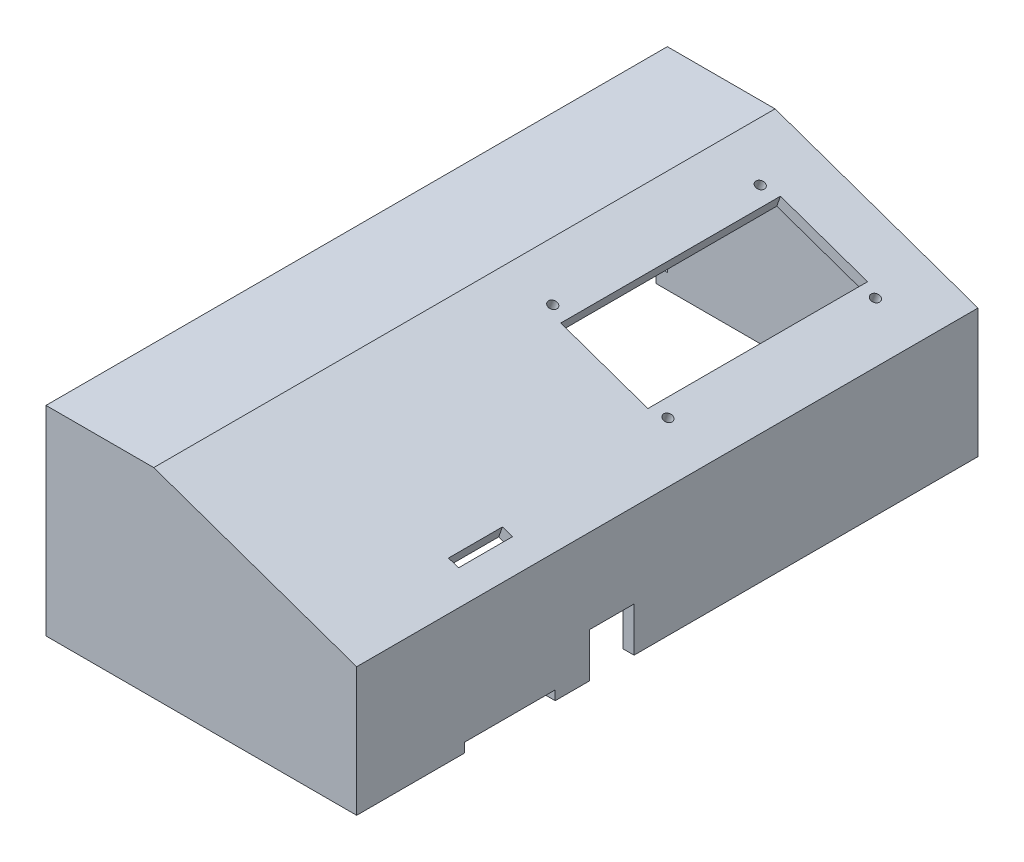
SolidWorks part; units mm, degrees
ref_plane "Front Plane" through (0, 0, 0) normal (0, 0, 1) x (1, 0, 0)
ref_plane "Top Plane" through (0, 0, 0) normal (0, 1, 0) x (1, 0, 0)
ref_plane "Right Plane" through (0, 0, 0) normal (1, 0, 0) x (0, 0, -1)
sketch "Sketch1" plane through (0, 0, 0) normal (0, 0, 1) x (1, 0, 0)
  line L0 (0, 0) -> (0, 90)
  line L1 (0, 90) -> (48.55, 90)
  line L2 (140, 58) -> (140, 0)
  line L3 (140, 0) -> (0, 0)
  line L4 (48.55, 90) -> (140, 58)
  dimension "D1" = 58
  dimension "D2" = 140
  dimension "D3" = 90
  dimension "D4" = 48.55
extrude "Boss-Extrude1" add sketch "Sketch1" along normal blind 280 contours L4 L2 L3 L0 L1
ref_plane "Plane1" through (0, 0, 275) normal (0, 0, 1) x (1, 0, 0)
sketch "Sketch2" plane through (0, 0, 275) normal (0, 0, 1) x (1, 0, 0)
  line L5 (47.7005, 85) -> (5, 85)
  line L6 (5, 85) -> (5, 0)
  line L8 (135, 0) -> (135, 54.4523)
  line L9 (135, 54.4523) -> (47.7005, 85)
  line L15 (5, 0) -> (135, 0)
extrude "Cut-Extrude1" cut sketch "Sketch2" against normal blind 270
sketch "Sketch3" plane through (0, 0, 0) normal (-1, 0, 0) x (0, 0, 1)
  line L5 (5, 0) -> (275, 0)
  line L8 (5, 85) -> (5, 5)
  line L9 (5, 5) -> (275, 5)
  line L10 (275, 5) -> (275, 85)
  line L11 (275, 85) -> (5, 85)
  line L12 (5, 85) -> (5, 0)
  line L14 (275, 0) -> (275, 85)
  line L15 (275, 85) -> (5, 85)
  dimension "D1" = 5
extrude "Cut-Extrude2" cut sketch "Sketch3" against normal blind 10
sketch "Sketch5" plane through (0, 0, 0) normal (0, 0, -1) x (-1, 0, 0)
  line L0 (-124, 0) -> (-124, 20)
  line L1 (-140, 0) -> (0, 0) construction
  line L2 (-124, 20) -> (-104, 20)
  line L3 (-104, 20) -> (-104, 0)
  line L4 (-124, 0) -> (-104, 0)
  line L5 (-140, 58) -> (-140, 0) construction
  dimension "D1" = 20
  dimension "D2" = 20
  dimension "D3" = 16
extrude "Cut-Extrude3" cut sketch "Sketch5" against normal blind 10 contours L2 L3 L4 L0
sketch "Sketch6" plane through (140, 0, 0) normal (1, 0, 0) x (0, 0, -1)
  line L0 (-280, 0) -> (0, 0) construction
  line L1 (-155, 20) -> (-175, 20)
  line L2 (-155, 20) -> (-155, -20)
  line L3 (-155, -20) -> (-175, -20)
  line L4 (-175, 20) -> (-175, -20)
  line L5 (-155, 20) -> (-175, -20) construction
  line L6 (-155, -20) -> (-175, 20) construction
  line L7 (-280, 58) -> (-280, 0) construction
  point P0 (-165, 0)
  dimension "D1" = 115
  dimension "D2" = 40
  dimension "D3" = 20
extrude "Cut-Extrude4" cut sketch "Sketch6" against normal blind 10
sketch "Sketch7" plane through (140, 0, 0) normal (1, 0, 0) x (0, 0, -1)
  line L0 (-280, 0) -> (-175, 0) construction
  line L1 (-231.3624, -4.2335) -> (-190.5351, -4.2335)
  line L2 (-231.3624, -4.2335) -> (-231.3624, 4.2335)
  line L3 (-231.3624, 4.2335) -> (-190.5351, 4.2335)
  line L4 (-190.5351, -4.2335) -> (-190.5351, 4.2335)
  line L5 (-231.3624, -4.2335) -> (-190.5351, 4.2335) construction
  line L6 (-231.3624, 4.2335) -> (-190.5351, -4.2335) construction
  point P0 (-210.9487, 0)
extrude "Cut-Extrude5" cut sketch "Sketch7" against normal blind 10
sketch "Sketch8" plane through (0, 0, 0) normal (0, 0, -1) x (-1, 0, 0)
  line L0 (0, 0) -> (0, 90) construction
  line L1 (5, 75) -> (-5, 75)
  line L2 (5, 75) -> (5, 66.9047)
  line L3 (5, 66.9047) -> (-5, 66.9047)
  line L4 (-5, 75) -> (-5, 66.9047)
  line L5 (5, 75) -> (-5, 66.9047) construction
  line L6 (5, 66.9047) -> (-5, 75) construction
  line L15 (0, 90) -> (-48.55, 90) construction
  line L16 (5, 45) -> (5, 36.9047)
  line L17 (5, 45) -> (-5, 45)
  line L18 (-5, 45) -> (-5, 36.9047)
  line L19 (5, 36.9047) -> (-5, 36.9047)
  line L20 (5, 15) -> (5, 6.9047)
  line L21 (5, 15) -> (-5, 15)
  line L22 (-5, 15) -> (-5, 6.9047)
  line L23 (5, 6.9047) -> (-5, 6.9047)
  point P0 (0, 70.9524)
  dimension "D1" = 10
  dimension "D2" = 15
  dimension "D3" = 3
extrude "Cut-Extrude6" cut sketch "Sketch8" against normal blind 10
sketch "Sketch9" plane through (33.3533, 95.3176, 0) normal (0.3303, 0.9439, 0) x (0.9439, -0.3303, 0)
  line L4 (43.803, -122.729) -> (85.403, -122.729)
  line L6 (85.403, -23.729) -> (85.403, -122.729)
  line L7 (85.403, -23.729) -> (43.803, -23.729)
  line L8 (43.803, -23.729) -> (43.803, -122.729)
extrude "Cut-Extrude7" cut sketch "Sketch9" against normal blind 10
sketch "Sketch10" plane through (31.7019, 90.5982, 0) normal (-0.3303, -0.9439, 0) x (0.9439, -0.3303, 0)
  circle A0 centre (91.803, 26.229) radius 2
  circle A1 centre (36.803, 26.229) radius 2
  circle A2 centre (91.803, 119.729) radius 2
  circle A3 centre (36.803, 119.729) radius 2
  dimension "D1" = 4
  dimension "D2" = 4
  dimension "D3" = 4
  dimension "D4" = 4
extrude "Cut-Extrude8" cut sketch "Sketch10" against normal blind 10
sketch "Sketch11" plane through (33.3533, 95.3176, 0) normal (0.3303, 0.9439, 0) x (0.9439, -0.3303, 0)
  line L1 (95.936, -222.5216) -> (100.7053, -222.5216)
  line L2 (95.936, -222.5216) -> (95.936, -198.228)
  line L3 (95.936, -198.228) -> (100.7053, -198.228)
  line L4 (100.7053, -222.5216) -> (100.7053, -198.228)
  line L5 (95.936, -222.5216) -> (100.7053, -198.228) construction
  line L6 (95.936, -198.228) -> (100.7053, -222.5216) construction
  point P0 (98.3206, -210.3748)
  point P5 (97.1975, -210.3748)
  point P6 (97.6526, -210.3748)
  point P7 (97.1975, -210.3748)
  point P8 (97.1975, -210.3748)
  point P10 (97.1975, -210.3748)
  point P12 (97.1975, -210.3748)
  dimension "D1" = 24.2936
extrude "Cut-Extrude9" cut sketch "Sketch11" against normal blind 10
